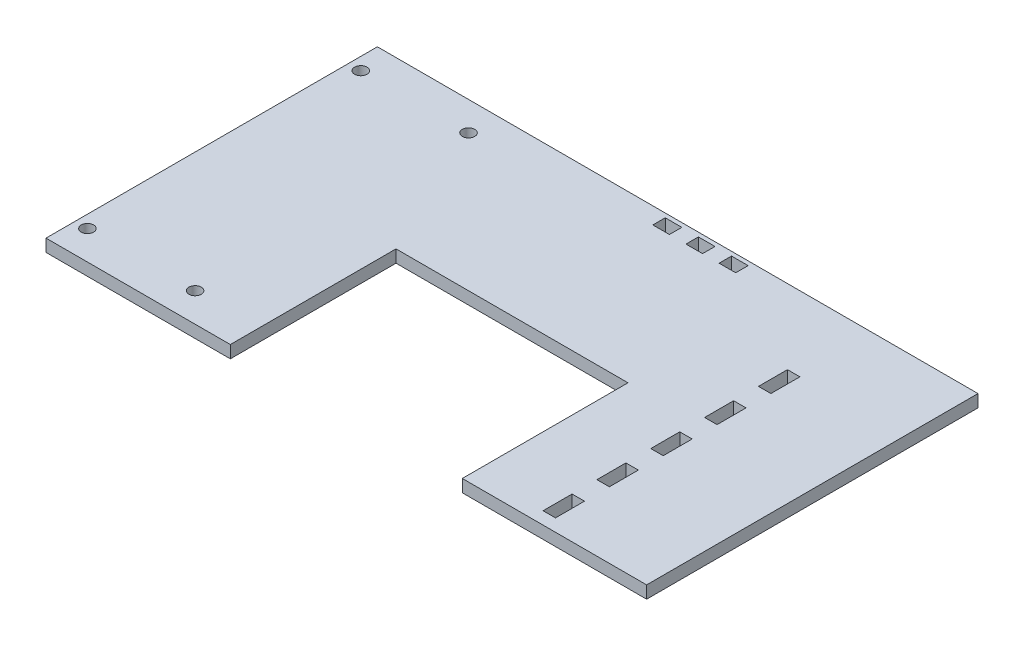
SolidWorks part; units mm, degrees
ref_plane "Front Plane" through (0, 0, 0) normal (0, 0, 1) x (1, 0, 0)
ref_plane "Top Plane" through (0, 0, 0) normal (0, 1, 0) x (1, 0, 0)
ref_plane "Right Plane" through (0, 0, 0) normal (1, 0, 0) x (0, 0, -1)
sketch "Sketch1" plane through (0, 0, 0) normal (0, 1, 0) x (1, 0, 0)
  line L0 (44.5, 9) -> (44.5, 2)
  line L1 (-72.5, -40) -> (-28, -40)
  line L2 (-72.5, -40) -> (-72.5, 40)
  line L3 (-72.5, 40) -> (72.5, 40)
  line L4 (72.5, -40) -> (72.5, 40)
  line L5 (-72.5, -40) -> (72.5, 40) construction
  line L6 (-72.5, 40) -> (72.5, -40) construction
  line L7 (44.5, 22) -> (47.5, 22)
  line L8 (44.5, 22) -> (44.5, 15)
  line L9 (44.5, 15) -> (47.5, 15)
  line L10 (47.5, 22) -> (47.5, 15)
  line L11 (44.5, 22) -> (47.5, 15) construction
  line L12 (44.5, 15) -> (47.5, 22) construction
  line L13 (44.5, 9) -> (47.5, 9)
  line L14 (47.5, 9) -> (47.5, 2)
  line L15 (44.5, 2) -> (47.5, 2)
  line L16 (44.5, -4) -> (44.5, -11)
  line L17 (44.5, -4) -> (47.5, -4)
  line L18 (47.5, -4) -> (47.5, -11)
  line L19 (44.5, -11) -> (47.5, -11)
  line L20 (44.5, -17) -> (44.5, -24)
  line L21 (44.5, -17) -> (47.5, -17)
  line L22 (47.5, -17) -> (47.5, -24)
  line L23 (44.5, -24) -> (47.5, -24)
  line L24 (44.5, -30) -> (44.5, -37)
  line L25 (44.5, -30) -> (47.5, -30)
  line L26 (47.5, -30) -> (47.5, -37)
  line L27 (44.5, -37) -> (47.5, -37)
  line L28 (-28, -40) -> (-28, 0)
  line L29 (-2, 39) -> (2, 39)
  line L30 (-2, 39) -> (-2, 36)
  line L31 (-2, 36) -> (2, 36)
  line L32 (2, 39) -> (2, 36)
  line L33 (-2, 39) -> (2, 36) construction
  line L34 (-2, 36) -> (2, 39) construction
  line L35 (0, 0) -> (9.2735, 0) construction
  line L36 (-28, 0) -> (28, 0)
  line L37 (28, 0) -> (28, -40)
  line L38 (28, -40) -> (72.5, -40)
  line L40 (6, 39) -> (10, 39)
  line L41 (6, 39) -> (6, 36)
  line L42 (6, 36) -> (10, 36)
  line L43 (10, 39) -> (10, 36)
  line L44 (0, 37.5) -> (0, 38.6806) construction
  line L45 (14, 39) -> (18, 39)
  line L46 (14, 39) -> (14, 36)
  line L47 (14, 36) -> (18, 36)
  line L48 (18, 39) -> (18, 36)
  circle A0 centre (-69.5, 33) radius 1.5
  circle A1 centre (-43.5, 33) radius 1.5
  circle A2 centre (-43.5, -33) radius 1.5
  circle A3 centre (-69.5, -33) radius 1.5
  point P0 (0, 0)
  point P11 (0, 37.5)
  point P32 (0, 0)
  point P57 (0, 0)
  dimension "D10" = 3
  dimension "D1" = 145
  dimension "D2" = 80
  dimension "D3" = 4
  dimension "D4" = 7
  dimension "D5" = 3
  dimension "D7" = 6
  dimension "D8" = 3
  dimension "D9" = 1
  dimension "D11" = 26
  dimension "D12" = 66
  dimension "D13" = 7
  dimension "D14" = 3
  dimension "D16" = 25
  dimension "D17" = 56
  dimension "D18" = 40
  dimension "D19" = 3
  dimension "D6" = 5
  dimension "D15" = 3
extrude "Boss-Extrude1" add sketch "Sketch1" along normal blind 3
